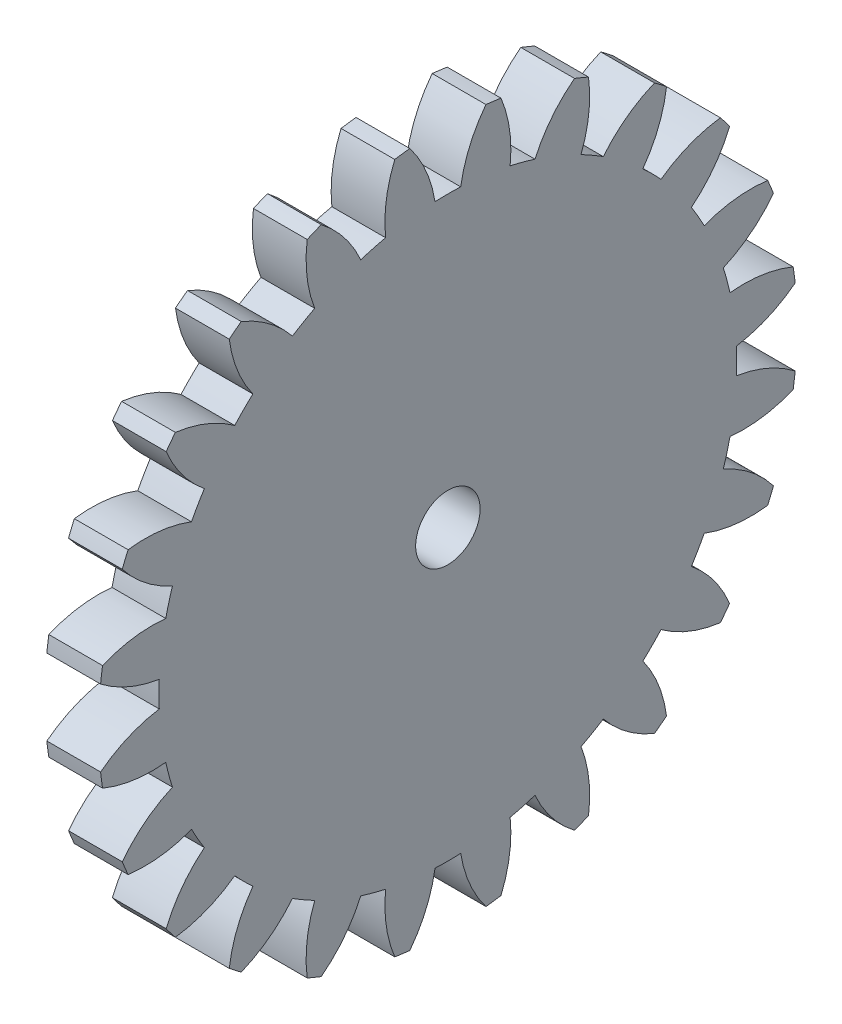
SolidWorks part; units mm, degrees
ref_plane "Plane1" through (0, 0, 0) normal (0, 0, 1) x (1, 0, 0)
ref_plane "Plane2" through (0, 0, 0) normal (0, 1, 0) x (1, 0, 0)
ref_plane "Plane3" through (0, 0, 0) normal (1, 0, 0) x (0, 0, -1)
sketch "HoldingSke" plane through (0, 0, 0) normal (0, 1, 0) x (1, 0, 0)
  line L0 (0, 0) -> (0.3654, -0.1627)
  line L1 (-15, 0) -> (100, 0) construction
  line L2 (0, 0) -> (-2.1039, 2.3779)
  line L3 (0, 0) -> (-11.863, 4.5341)
  line L4 (0, 0) -> (7.8894, 3.5126)
  line L5 (0, 0) -> (-46.8476, -17.4728)
  line L6 (0, 0) -> (-4.1448, -2.7965)
  line L7 (-2.1039, 2.3779) -> (8.6586, 51.2059)
  line L8 (-76.2, 54.61) -> (-75.2, 54.61)
  line L9 (-71.009, 38.7566) -> (-53.1078, 45.2721)
  line L10 (-76.2, 71.12) -> (104.1128, 71.12)
  line L11 (0, 0) -> (-5, 0)
  line L12 (-76.2, 101.6) -> (-76.113, 101.6)
  line L13 (24.9733, 27.94) -> (52.9518, 28.4284)
  line L14 (24.9733, 27.94) -> (24.9743, 27.94)
  line L15 (24.9733, 27.94) -> (100.4006, 29.5858)
  line L16 (-63.627, -2.5) -> (-12.827, -2.5)
  circle A0 centre (0, 0) radius 3
  circle A1 centre (0, 0) radius 26.874
  circle A2 centre (0, 0) radius 37.5
  circle A3 centre (0, 0) radius 3
  dimension "Hub_dia" = 75
  dimension "Bore" = 6
  dimension "MBD" = 6
  dimension "Pitch" = 0.4
  dimension "Overall_len" = 50
  dimension "OAL" = 50.0001
  dimension "T_dim" = 1
  dimension "Ap" = 20
  dimension "H" = 19.05
  dimension "Pitch_radius" = 180.3128
  dimension "Backlash" = 0.087
  dimension "Addendum_fac" = 1
  dimension "Dedendum_fac" = 1.25
  dimension "Clearance_fac" = 0.25
  dimension "Dedendum_add" = 0.001
  dimension "Module" = 2.5
sketch "BasProSke" plane through (0, 0, 0) normal (0, 1, 0) x (1, 0, 0)
  line L0 (-10, 0) -> (60, 0) construction
  line L1 (0, 0) -> (0, 32.5)
  line L2 (0, 0) -> (5, 0)
  line L3 (5, 0) -> (5, 32.5)
  line L4 (5, 32.5) -> (0, 32.5)
revolve "Base-Revolve" add sketch "BasProSke" angle 360 about L0
sketch "TooCutSke" plane through (0, 0, 0) normal (1, 0, 0) x (0, 0, -1)
  line L1 (0, 0) -> (0, 107) construction
  line L2 (0, 0) -> (-2.1143, 29.9254) construction
  line L3 (0, 0) -> (-7.8173, 59.3783) construction
  line L4 (-2.1143, 29.9254) -> (-3.9087, 29.6892) construction
  arc A0 (1.1963, 26.8474) -> (-1.1963, 26.8474) centre (0, 0) ccw
  arc A1 (3.5598, 32.33) -> (-3.5598, 32.33) centre (0, 0) ccw
  circle A2 centre (0, 0) radius 30 construction
  circle A3 centre (0, 0) radius 28.1908 construction
  arc A4 (-1.1963, 26.8474) -> (-3.5598, 32.33) centre (-13.0513, 24.9877) ccw
  arc A5 (3.5598, 32.33) -> (1.1963, 26.8474) centre (13.0513, 24.9877) ccw
extrude "ToothCut" cut sketch "TooCutSke" along normal through all
fillet "Breaks" [suppressed] radius 0.05
fillet "RootFillets" [suppressed] radius 0.626
pattern_circular "TeethCuts" count 24 every 15 about axis through (-10, 0, 0) along (1, 0, 0) of "ToothCut", "RootFillets", "Breaks"
sketch "HubNeaOneSke" plane through (0, 0, 0) normal (-1, 0, 0) x (0, 0, 1)
  circle A0 centre (0, 0) radius 26.874
extrude "HubNearOne" [suppressed] add sketch "HubNeaOneSke" along normal blind 45.0001
sketch "HubNeaBotSke" plane through (0, 0, 0) normal (-1, 0, 0) x (0, 0, 1)
  circle A0 centre (0, 0) radius 26.874
extrude "HubNearBoth" [suppressed] add sketch "HubNeaBotSke" along normal blind 22.5
ref_plane "FarPln" through (5, 0, 0) normal (1, 0, 0) x (0, 0, -1)
sketch "HubFarSke" plane through (5, 0, 0) normal (1, 0, 0) x (0, 0, -1)
  circle A0 centre (0, 0) radius 26.874
extrude "HubFar" [suppressed] add sketch "HubFarSke" along normal blind 22.5
sketch "BorSke" plane through (0, 0, 0) normal (1, 0, 0) x (0, 0, -1)
  circle A0 centre (0, 0) radius 3
  dimension "Diameter" = 6
extrude "Bore" cut sketch "BorSke" along normal mid plane 100.0001
sketch "KeySke" plane through (0, 0, 0) normal (1, 0, 0) x (0, 0, -1)
  line L0 (-1, 0) -> (-1, 4)
  line L1 (-1, 4) -> (1, 4)
  line L2 (1, 4) -> (1, 0)
  line L3 (0, 0) -> (0, 34) construction
  line L4 (-1, 0) -> (1, 0)
  dimension "Offset" = 4
  dimension "Width" = 2
extrude "Keyway" [suppressed] cut sketch "KeySke" along normal mid plane 100.0001
pattern_circular "Keyway2" [suppressed] count 2 every 90 about axis through (-10, 0, 0) along (1, 0, 0)
equation "' \"Module@HoldingSke\" = 6.35"
equation "' \"Num_teeth@HoldingSke\" = 12"
equation "' \"Ap@HoldingSke\" =  20"
equation "' \"Ap@HoldingSke\" = 20"
equation "' \"Width@HoldingSke\" = 0.5 * 25.4"
equation "' \"Hub_dia@HoldingSke\"= 1 * 25.4"
equation "' \"Hub_dia@HoldingSke\" = 1 * 25.4"
equation "' \"Overall_len@HoldingSke\" = 1.0 * 25.4"
equation "' \"Bore@HoldingSke\" = 0.75 * 25.4"
equation "' \"T_dim@HoldingSke\" = 0.1 * 25.4"
equation "' \"Width@KeySke\" = 0.25 * 25.4"
equation "' \"Show_teeth@HoldingSke\" = 13"
equation "' \"Backlash@HoldingSke\" = 0.009 * 25.4"
equation "' \"Addendum_fac@HoldingSke\" = 1.0"
equation "' \"Dedendum_fac@HoldingSke\" = 1.25"
equation "' \"Dedendum_add@HoldingSke\" = 0.00005 * 25.4"
equation "' \"Clearance_fac@HoldingSke\" = 0.25"
equation "\"Pitch@HoldingSke\" = 1 / \"Module@HoldingSke\""
equation "\"Overcut_dia@TooCutSke\" = (\"Num_teeth@HoldingSke\" + 2 * \"Addendum_fac@HoldingSke\") / \"Pitch@HoldingSke\" + 0.002 * 25.4"
equation "\"Pitch_dia@TooCutSke\" = \"Num_teeth@HoldingSke\" / \"Pitch@HoldingSke\""
equation "\"Base_dia@TooCutSke\" = \"Num_teeth@HoldingSke\" / \"Pitch@HoldingSke\" * cos((\"Ap@HoldingSke\"  * 3.14159265 / 180))"
equation "\"Root_dia@TooCutSke\" = (\"Num_teeth@HoldingSke\" + 2) / \"Pitch@HoldingSke\" - 2 * (\"Addendum_fac@HoldingSke\" + \"Dedendum_fac@HoldingSke\") / \"Pitch@HoldingSke\" - \"Dedendum_add@HoldingSke\" * 2"
equation "\"Half_ang@TooCutSke\" = 180 / \"Num_teeth@HoldingSke\""
equation "\"Half_CT@TooCutSke\" = \"Num_teeth@HoldingSke\" / \"Pitch@HoldingSke\" * sin((3.14159265 / 2 / \"Num_teeth@HoldingSke\")) / 2 - 7 * \"Backlash@HoldingSke\" / 4"
equation "\"Flank_rad@TooCutSke\" = \"Num_teeth@HoldingSke\" / \"Pitch@HoldingSke\" / 5"
equation "\"Radius@RootFillets\" = \"Clearance_fac@HoldingSke\" / \"Pitch@HoldingSke\" + \"Dedendum_add@HoldingSke\""
equation "\"Break_rad@Breaks\" = 0.02 / \"Pitch@HoldingSke\""
equation "\"Thickness@HoldingSke\" = \"Width@HoldingSke\""
equation "\"OAL@HoldingSke\" = \"Thickness@HoldingSke\""
equation "\"MHD@HoldingSke\" = (\"Num_teeth@HoldingSke\" + 2) / \"Pitch@HoldingSke\" - 2 * (\"Addendum_fac@HoldingSke\" + \"Dedendum_fac@HoldingSke\")  / \"Pitch@HoldingSke\" - \"Dedendum_add@HoldingSke\" * 2"
equation "\"MBD@HoldingSke\" = (\"Num_teeth@HoldingSke\" + 2) / \"Pitch@HoldingSke\" - 2 * (\"Addendum_fac@HoldingSke\" + \"Dedendum_fac@HoldingSke\")  / \"Pitch@HoldingSke\" - \"Dedendum_add@HoldingSke\" * 2 - 0.002 * 25.4"
equation "\"MHD@HoldingSke\" = ((sgn( \"MHD@HoldingSke\" - \"Hub_dia@HoldingSke\" )-1)*( \"MHD@HoldingSke\" - \"Hub_dia@HoldingSke\" ))/-2+ \"Hub_dia@HoldingSke\""
equation "\"MBD@HoldingSke\" = ((sgn( \"MBD@HoldingSke\" - \"Bore@HoldingSke\" )-1)*( \"MBD@HoldingSke\" - \"Bore@HoldingSke\" ))/-2+ \"Bore@HoldingSke\""
equation "\"OAL@HoldingSke\" = ((sgn( \"OAL@HoldingSke\" - \"Overall_len@HoldingSke\" )+1)*( \"OAL@HoldingSke\" - \"Overall_len@HoldingSke\" ))/2 + \"Overall_len@HoldingSke\" + 0.000002 * 25.4"
equation "\"Num_teeth@TeethCuts\" = int( \"Show_teeth@HoldingSke\" ) + 1"
equation "\"Num_teeth@TeethCuts\" = ((sgn( \"Num_teeth@TeethCuts\" - \"Num_teeth@HoldingSke\" )-1)*( \"Num_teeth@TeethCuts\" - \"Num_teeth@HoldingSke\" ))/-2+ \"Num_teeth@HoldingSke\""
equation "\"Num_teeth@TeethCuts\" = ((sgn( \"Num_teeth@TeethCuts\" - 2.0)+1)*( \"Num_teeth@TeethCuts\" - 2.0))/2 +2.0"
equation "\"Angle@TeethCuts\" = 360.0 / \"Num_teeth@HoldingSke\""
equation "\"Diameter@BasProSke\" = (\"Num_teeth@HoldingSke\" + 2 * \"Addendum_fac@HoldingSke\") / \"Pitch@HoldingSke\""
equation "\"Thickness@BasProSke\"  = \"Thickness@HoldingSke\""
equation "' \"Fillet_rad@BasProSke\" =  \"Thickness@HoldingSke\" * 0.05"
equation "' \"Fillet_rad@BasProSke\" = \"Thickness@HoldingSke\" * 0.05"
equation "\"MHD@HoldingSke\" = ((sgn( \"MHD@HoldingSke\" - \"Root_dia@TooCutSke\" )-1)*( \"MHD@HoldingSke\" - \"Root_dia@TooCutSke\" ))/-2+ \"Root_dia@TooCutSke\""
equation "\"Diameter@HubNeaOneSke\" = \"MHD@HoldingSke\""
equation "\"Length@HubNearOne\" = \"OAL@HoldingSke\" - \"Thickness@BasProSke\""
equation "\"Diameter@HubNeaBotSke\" = \"MHD@HoldingSke\""
equation "\"Length@HubNearBoth\" = ( \"OAL@HoldingSke\" - \"Thickness@BasProSke\" ) / 2.0"
equation "\"Thickness@FarPln\" = \"Thickness@BasProSke\""
equation "\"Diameter@HubFarSke\" = \"MHD@HoldingSke\""
equation "\"Length@HubFar\" = ( \"OAL@HoldingSke\" - \"Thickness@BasProSke\" ) / 2.0"
equation "\"Diameter@BorSke\" = \"MBD@HoldingSke\""
equation "\"D1@Bore\" = \"OAL@HoldingSke\" * 2.0"
equation "\"D1@Keyway\" = \"OAL@HoldingSke\" * 2.0"
equation "\"Offset@KeySke\" = \"T_dim@HoldingSke\" + \"MBD@HoldingSke\" / 2.0"
